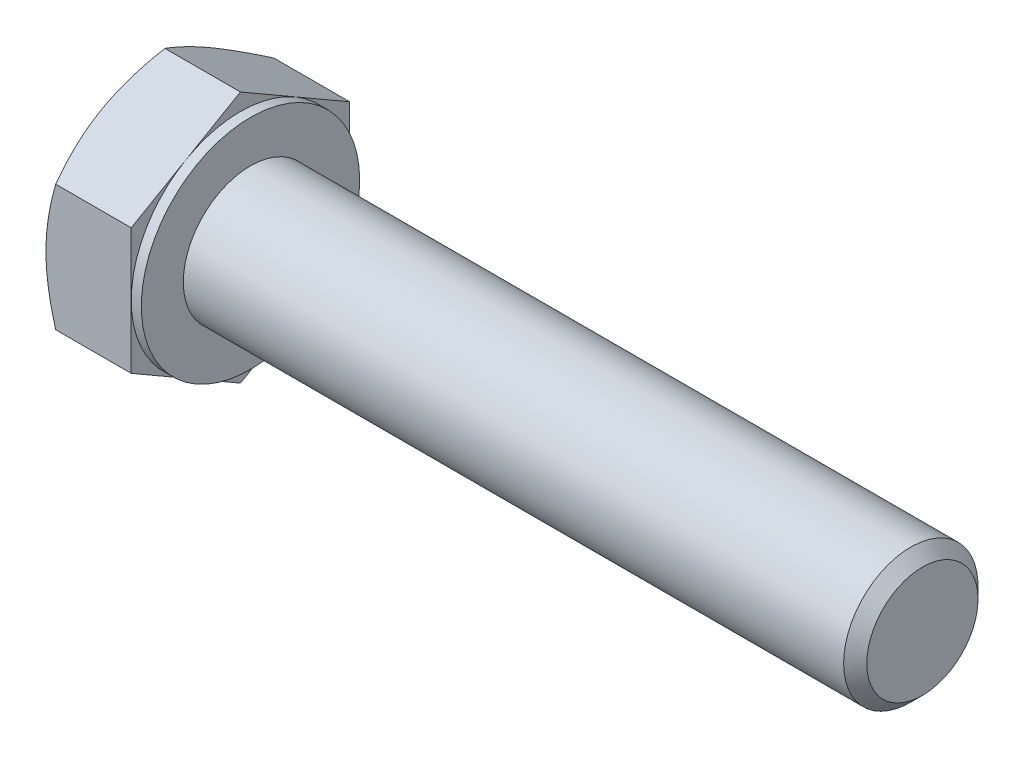
SolidWorks part; units mm, degrees
ref_plane "Plane1" through (0, 0, 0) normal (0, 0, 1) x (1, 0, 0)
ref_plane "Plane2" through (0, 0, 0) normal (0, 1, 0) x (1, 0, 0)
ref_plane "Plane3" through (0, 0, 0) normal (1, 0, 0) x (0, 0, -1)
sketch "Sketch1" plane through (0, 0, 0) normal (1, 0, 0) x (0, 0, -1)
  line L0 (6.5, 3.7528) -> (6.5, -3.7528)
  line L1 (-6.5, 3.7528) -> (-6.5, -3.7528)
  line L2 (6.5, -3.7528) -> (0, -7.5056)
  line L3 (0, -7.5056) -> (-6.5, -3.7528)
  line L4 (6.5, 3.7528) -> (0, 7.5056)
  line L5 (0, 7.5056) -> (-6.5, 3.7528)
  dimension "Width_flats" = 13
  dimension "D2" = 120
  dimension "D3" = 6.5
  dimension "D4" = 6.5
  dimension "D5" = 6.5
extrude "BaseHead" add sketch "Sketch1" along normal blind 5.675
sketch "BodySke" plane through (0, 0, 0) normal (0, 0, 1) x (1, 0, 0)
  line L0 (0, 3.7528) -> (0, -3.7528) construction
  line L1 (0, 0) -> (45.675, 0)
  line L2 (0, 0) -> (0, 4)
  line L3 (0, 4) -> (44.9845, 4)
  line L4 (45.675, 0) -> (45.675, 3.3095)
  line L5 (5.675, 7.5056) -> (5.675, 3.7528) construction
  line L6 (45.675, 3.3095) -> (44.9845, 4)
  line L7 (0, 0) -> (96.52, 0) construction
  line L8 (45.675, -3.3095) -> (44.9845, -4) construction
  line L9 (0, -4) -> (44.9845, -4) construction
  line L10 (6.925, 15.24) -> (6.925, -1.27) construction
  line L11 (23.675, 15.24) -> (23.675, -1.27) construction
  line L12 (5.675, 3.7528) -> (5.675, -3.7528) construction
  dimension "Length" = 40
  dimension "Body_ch_ang" = 45
  dimension "Diameter" = 8
  dimension "Minor_dia" = 6.619
  dimension "Advance" = 1.25
  dimension "Thread_nom" = 22
revolve "BaseBody" add sketch "BodySke"
cosmetic thread "ThreadCosmetic" [suppressed]
fillet "HeadFillet" [suppressed] radius 0.4
cosmetic thread "裝飾螺紋線1"
sketch "Sketch3" plane through (0, 0, 0) normal (0, 0, 1) x (1, 0, 0)
  line L0 (0, 6.5) -> (3.4673, 12.5056)
  line L1 (0, 7.5056) -> (0, 3.7528) construction
  line L2 (3.4673, 12.5056) -> (3.4673, 17.5056)
  line L3 (3.4673, 17.5056) -> (-10, 17.5056)
  line L4 (-10, 17.5056) -> (-10, 6.5)
  line L5 (-10, 6.5) -> (0, 6.5)
  line L6 (0, 0) -> (99.06, 0) construction
  line L7 (5.675, 7.5056) -> (0, 7.5056) construction
  dimension "D1" = 6.5
  dimension "D2" = 5
  dimension "D3" = 10
  dimension "D4" = 5
  dimension "Head_ch_ang" = 30
revolve "HeadChamfer" cut sketch "Sketch3" angle 360 about L6
sketch "Sketch4" plane through (0, 0, 0) normal (0, 0, 1) x (1, 0, 0)
  line L1 (5.675, 7.5056) -> (5.675, 3.7528) construction
  line L2 (5.675, 6.5) -> (5.075, 6.5)
  line L3 (5.675, 6.5) -> (5.675, 17.5056)
  line L4 (5.675, 17.5056) -> (5.075, 17.5056)
  line L5 (0, 0) -> (95.25, 0) construction
  line L6 (0, 0) -> (96.52, 0) construction
  line L7 (5.075, 6.5) -> (5.075, 17.5056)
  line L8 (5.675, 7.5056) -> (0.5806, 7.5056) construction
  dimension "D1" = 13
  dimension "D2" = 10
  dimension "Bearing_ht" = 0.6
revolve "BearingFace" cut sketch "Sketch4" angle 360 about L5
sketch "ThdSchSke" plane through (0, 0, 0) normal (0, 0, 1) x (1, 0, 0)
  line L0 (23.675, -3.3095) -> (23.1915, -4)
  line L1 (23.675, -3.3095) -> (24.1585, -4)
  line L2 (24.1585, -4) -> (24.1585, -5)
  line L3 (-3.175, 0) -> (5.1513, 0) construction
  line L5 (24.1585, -5) -> (23.1915, -5)
  line L6 (23.1915, -5) -> (23.1915, -4)
  dimension "Thread_minor" = 6.619
  dimension "Diameter" = 8
  dimension "Start" = 23.675
  dimension "SideAngle" = 55
  dimension "VeeAngle" = 70
  dimension "Overcut" = 10
revolve "ThreadSchematic" [suppressed] cut sketch "ThdSchSke" angle 360 about L3
pattern_linear "ThdSchPat" [suppressed]
equation "\"D3@Sketch1\" = \"Width_flats@Sketch1\" / 2"
equation "\"D4@Sketch1\" = \"D3@Sketch1\""
equation "\"D5@Sketch1\" = \"D4@Sketch1\""
equation "\"Thread_minor@ThreadCosmetic\" = \"Minor_dia@BodySke\""
equation "\"D1@Sketch3\" = \"Width_flats@Sketch1\" / 2"
equation "\"D1@Sketch4\" = \"Width_flats@Sketch1\""
equation "\"Thread_length@ThreadCosmetic\" = ((sgn( (\"Length@BodySke\" - \"Advance@BodySke\" ) - \"Thread_nom@BodySke\" )-1)*( (\"Length@BodySke\" - \"Advance@BodySke\" ) - \"Thread_nom@BodySke\" ))/-2+ \"Thread_nom@BodySke\""
equation "\"Thread_minor@ThdSchSke\" = \"Minor_dia@BodySke\""
equation "\"Diameter@ThdSchSke\" = \"Diameter@BodySke\""
equation "\"Overcut@ThdSchSke\" = \"Diameter@BodySke\" * 1.25"
equation "\"Start@ThdSchSke\" = \"Head_ht@BaseHead\" + \"Length@BodySke\" - \"Thread_length@ThreadCosmetic\"  '---Non-countersunk---"
equation "\"Num_threads@ThdSchPat\" = int( \"Thread_length@ThreadCosmetic\" / \"Advance@BodySke\" + 0.999 )  + 1"
equation "\"Advance@ThdSchPat\" = \"Thread_length@ThreadCosmetic\" /  (\"Num_threads@ThdSchPat\" - 1) 'relax it"
equation "\"Num_threads@ThdSchPat\" = \"Num_threads@ThdSchPat\" - sgn( \"Num_threads@ThdSchPat\" - 1) '---chamfered tips only---"
